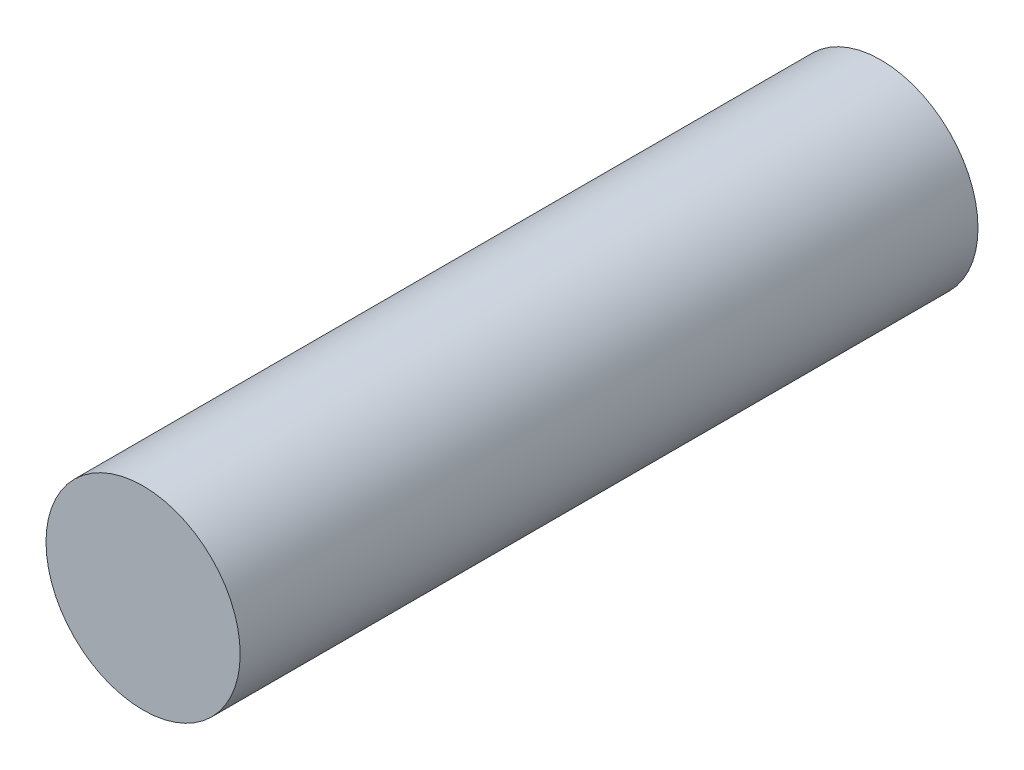
SolidWorks part; units mm, degrees
ref_plane "Front Plane" through (0, 0, 0) normal (0, 0, 1) x (1, 0, 0)
ref_plane "Top Plane" through (0, 0, 0) normal (0, 1, 0) x (1, 0, 0)
ref_plane "Right Plane" through (0, 0, 0) normal (1, 0, 0) x (0, 0, -1)
sketch "Sketch1" plane through (0, 0, 0) normal (0, 0, 1) x (1, 0, 0)
  circle A0 centre (0, 0) radius 1.5875
  dimension "D1" = 3.175
extrude "Boss-Extrude1" add sketch "Sketch1" along normal blind 12.065 contours A0
